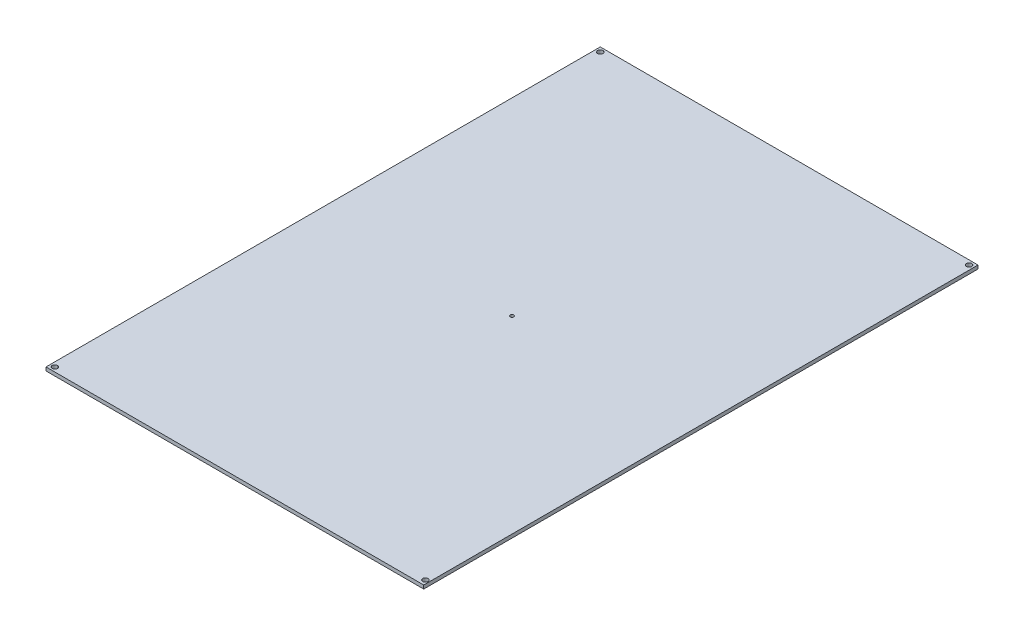
SolidWorks part; units mm, degrees
other "Камера1"
ref_plane "Спереди" through (0, 0, 0) normal (0, 0, 1) x (1, 0, 0)
ref_plane "Сверху" through (0, 0, 0) normal (0, 1, 0) x (1, 0, 0)
ref_plane "Справа" through (0, 0, 0) normal (1, 0, 0) x (0, 0, -1)
sketch "Эскиз1" plane through (0, 0, 0) normal (0, 1, 0) x (1, 0, 0)
  line L1 (-107, -157) -> (107, -157)
  line L2 (-107, -157) -> (-107, 157)
  line L3 (-107, 157) -> (107, 157)
  line L4 (107, -157) -> (107, 157)
  line L5 (-107, -157) -> (107, 157) construction
  line L6 (-107, 157) -> (107, -157) construction
  circle A0 centre (-104.5, 154.5) radius 1.5
  circle A1 centre (104.5, 154.5) radius 1.5
  circle A2 centre (105.0089, -154.0785) radius 1.5
  circle A3 centre (-104.4968, -154.4968) radius 1.5
  circle A4 centre (0, 0) radius 1
  point P0 (0, 0)
  point P11 (0, 0)
  point P14 (0, 0)
  point P17 (0, 0)
  point P20 (0, 0)
  dimension "D3" = 3.5355
  dimension "D4" = 3
  dimension "D6" = 3.5355
  dimension "D1" = 214
  dimension "D2" = 314
  dimension "D7" = 3.5355
  dimension "D5" = 3.54
extrude "Бобышка-Вытянуть1" add sketch "Эскиз1" along normal blind 2
